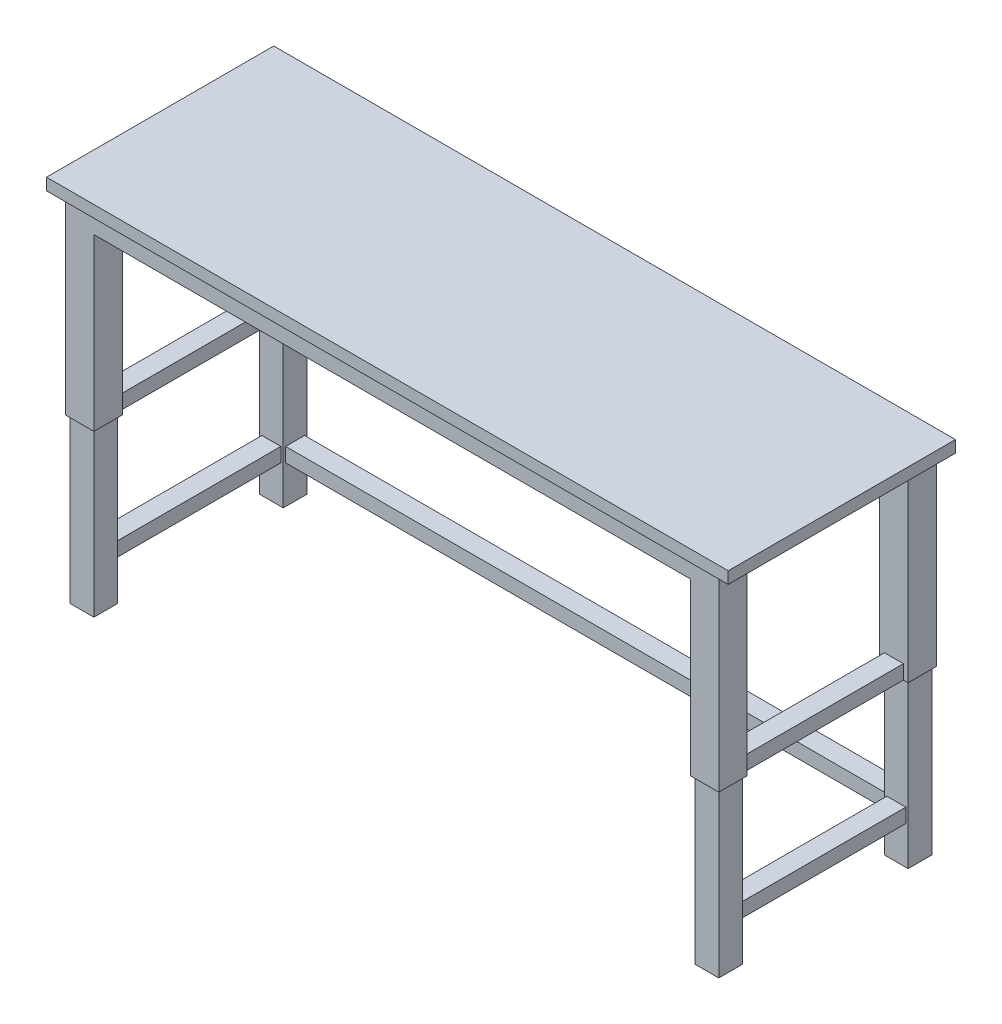
SolidWorks part; units mm, degrees
material "Plain Carbon Steel"
ref_plane "Front Plane" through (0, 0, 0) normal (0, 0, 1) x (1, 0, 0)
ref_plane "Top Plane" through (0, 0, 0) normal (0, 1, 0) x (1, 0, 0)
ref_plane "Right Plane" through (0, 0, 0) normal (1, 0, 0) x (0, 0, -1)
sketch "Sketch1" plane through (0, 0, 0) normal (0, 1, 0) x (1, 0, 0)
  line L1 (-914.4, -304.8) -> (914.4, -304.8)
  line L2 (-914.4, -304.8) -> (-914.4, 304.8)
  line L3 (-914.4, 304.8) -> (914.4, 304.8)
  line L4 (914.4, -304.8) -> (914.4, 304.8)
  line L5 (-914.4, -304.8) -> (914.4, 304.8) construction
  line L6 (-914.4, 304.8) -> (914.4, -304.8) construction
  point P0 (0, 0)
  dimension "D1" = 1828.8
  dimension "D2" = 609.6
extrude "Boss-Extrude1" add sketch "Sketch1" against normal blind 31.75
sketch "Sketch2" plane through (0, 0, 0) normal (1, 0, 0) x (0, 0, -1)
  line L0 (-304.8, -31.75) -> (304.8, -31.75) construction
  line L1 (-292.1, -31.75) -> (-215.9, -31.75)
  line L2 (-292.1, -31.75) -> (-292.1, -82.55)
  line L3 (-292.1, -82.55) -> (-215.9, -82.55)
  line L4 (-215.9, -31.75) -> (-215.9, -82.55)
  line L5 (215.9, -31.75) -> (292.1, -31.75)
  line L6 (215.9, -31.75) -> (215.9, -82.55)
  line L7 (215.9, -82.55) -> (292.1, -82.55)
  line L8 (292.1, -31.75) -> (292.1, -82.55)
  line L9 (-215.9, -31.75) -> (215.9, -31.75) construction
  line L10 (-304.8, -31.75) -> (-304.8, 0) construction
  point P10 (0, -31.75)
  dimension "D1" = 50.8
  dimension "D2" = 76.2
  dimension "D3" = 12.7
extrude "Boss-Extrude2" add sketch "Sketch2" along normal offset from surface 38.1 and the other way offset from surface (876.3 mm away) 38.1 separate body up to face at (914.4, -15.875, 0) other way up to face at (-914.4, -15.875, 0)
sketch "Sketch3" plane through (0, -31.75, 0) normal (0, 1, 0) x (1, 0, 0)
  line L0 (876.3, -215.9) -> (-876.3, -215.9) construction
  line L1 (876.3, -292.1) -> (800.1, -292.1)
  line L2 (876.3, -292.1) -> (876.3, -215.9)
  line L3 (876.3, -215.9) -> (800.1, -215.9)
  line L4 (800.1, -292.1) -> (800.1, -215.9)
  line L5 (876.3, 215.9) -> (-876.3, 215.9) construction
  line L6 (-876.3, -292.1) -> (-800.1, -292.1)
  line L7 (-876.3, -292.1) -> (-876.3, -215.9)
  line L8 (-876.3, -215.9) -> (-800.1, -215.9)
  line L9 (-800.1, -292.1) -> (-800.1, -215.9)
  line L10 (-876.3, 292.1) -> (-800.1, 292.1)
  line L11 (-876.3, 292.1) -> (-876.3, 215.9)
  line L12 (-876.3, 215.9) -> (-800.1, 215.9)
  line L13 (-800.1, 292.1) -> (-800.1, 215.9)
  line L15 (876.3, 292.1) -> (800.1, 292.1)
  line L16 (876.3, 292.1) -> (876.3, 215.9)
  line L17 (876.3, 215.9) -> (800.1, 215.9)
  line L18 (800.1, 292.1) -> (800.1, 215.9)
extrude "Boss-Extrude3" add sketch "Sketch3" against normal blind 508
sketch "Sketch4" plane through (0, 0, 215.9) normal (0, 0, -1) x (-1, 0, 0)
  line L1 (-863.6, -501.65) -> (-812.8, -501.65)
  line L2 (-863.6, -501.65) -> (-863.6, -539.75)
  line L3 (-863.6, -539.75) -> (-812.8, -539.75)
  line L4 (-812.8, -501.65) -> (-812.8, -539.75)
  line L5 (800.1, -539.75) -> (876.3, -539.75) construction
  line L6 (812.8, -539.75) -> (863.6, -539.75)
  line L7 (812.8, -539.75) -> (812.8, -501.65)
  line L8 (812.8, -501.65) -> (863.6, -501.65)
  line L9 (863.6, -539.75) -> (863.6, -501.65)
  line L10 (-876.3, -539.75) -> (-800.1, -539.75) construction
  point P12 (-838.2, -539.75)
  point P14 (838.2, -539.75)
  dimension "D1" = 50.8
  dimension "D2" = 38.1
extrude "Boss-Extrude4" add sketch "Sketch4" along normal up to surface (431.8 mm away) up to face at (0, -298.45, -215.9)
ref_plane "Plane1" through (0, -977.9, 0) normal (0, 1, 0) x (1, 0, 0)
sketch "Sketch6" plane through (0, -977.9, 0) normal (0, 1, 0) x (1, 0, 0)
  line L0 (-806.45, 285.75) -> (-869.95, 285.75)
  line L1 (-869.95, 285.75) -> (-869.95, 222.25)
  line L2 (-869.95, 222.25) -> (-806.45, 222.25)
  line L3 (-806.45, 222.25) -> (-806.45, 285.75)
  line L4 (-800.1, 292.1) -> (-876.3, 292.1)
  line L5 (-800.1, 215.9) -> (-800.1, 292.1)
  line L6 (-876.3, 215.9) -> (-800.1, 215.9)
  line L7 (-876.3, 292.1) -> (-876.3, 215.9)
  line L8 (-800.1, 292.1) -> (-876.3, 292.1) construction
  line L9 (-800.1, 215.9) -> (-800.1, 292.1) construction
  line L10 (-876.3, 215.9) -> (-800.1, 215.9) construction
  line L11 (-876.3, 292.1) -> (-876.3, 215.9) construction
  line L12 (-876.3, -292.1) -> (-800.1, -292.1)
  line L13 (-800.1, -292.1) -> (-800.1, -215.9)
  line L14 (-800.1, -215.9) -> (-876.3, -215.9)
  line L15 (-876.3, -215.9) -> (-876.3, -292.1)
  line L16 (-876.3, -292.1) -> (-800.1, -292.1) construction
  line L17 (-800.1, -292.1) -> (-800.1, -215.9) construction
  line L18 (-800.1, -215.9) -> (-876.3, -215.9) construction
  line L19 (-876.3, -215.9) -> (-876.3, -292.1) construction
  line L20 (800.1, -292.1) -> (876.3, -292.1)
  line L21 (800.1, -215.9) -> (800.1, -292.1)
  line L22 (876.3, -215.9) -> (800.1, -215.9)
  line L23 (876.3, -292.1) -> (876.3, -215.9)
  line L24 (800.1, -292.1) -> (876.3, -292.1) construction
  line L25 (800.1, -215.9) -> (800.1, -292.1) construction
  line L26 (876.3, -215.9) -> (800.1, -215.9) construction
  line L27 (876.3, -292.1) -> (876.3, -215.9) construction
  line L28 (876.3, 292.1) -> (800.1, 292.1)
  line L29 (800.1, 292.1) -> (800.1, 215.9)
  line L30 (800.1, 215.9) -> (876.3, 215.9)
  line L31 (876.3, 215.9) -> (876.3, 292.1)
  line L32 (876.3, 292.1) -> (800.1, 292.1) construction
  line L33 (800.1, 292.1) -> (800.1, 215.9) construction
  line L34 (800.1, 215.9) -> (876.3, 215.9) construction
  line L35 (876.3, 215.9) -> (876.3, 292.1) construction
  line L36 (-869.95, -285.75) -> (-806.45, -285.75)
  line L37 (-806.45, -285.75) -> (-806.45, -222.25)
  line L38 (-806.45, -222.25) -> (-869.95, -222.25)
  line L39 (-869.95, -222.25) -> (-869.95, -285.75)
  line L40 (806.45, -285.75) -> (869.95, -285.75)
  line L41 (869.95, -285.75) -> (869.95, -222.25)
  line L42 (869.95, -222.25) -> (806.45, -222.25)
  line L43 (806.45, -222.25) -> (806.45, -285.75)
  line L44 (869.95, 285.75) -> (806.45, 285.75)
  line L45 (806.45, 285.75) -> (806.45, 222.25)
  line L46 (806.45, 222.25) -> (869.95, 222.25)
  line L47 (869.95, 222.25) -> (869.95, 285.75)
  dimension "D5" = 63.5
  dimension "D1" = 0
  dimension "D2" = 0
  dimension "D3" = 0
  dimension "D4" = 0
extrude "Boss-Extrude5" add sketch "Sketch6" along normal up to surface (438.15 mm away) separate body up to face at (838.2, -539.75, 0)
sketch "Sketch7" plane through (0, 0, 222.25) normal (0, 0, -1) x (-1, 0, 0)
  line L1 (-863.6, -876.3) -> (-812.8, -876.3)
  line L2 (-863.6, -876.3) -> (-863.6, -838.2)
  line L3 (-863.6, -838.2) -> (-812.8, -838.2)
  line L4 (-812.8, -876.3) -> (-812.8, -838.2)
  line L5 (812.8, -876.3) -> (863.6, -876.3)
  line L6 (812.8, -876.3) -> (812.8, -838.2)
  line L7 (812.8, -838.2) -> (863.6, -838.2)
  line L8 (863.6, -876.3) -> (863.6, -838.2)
  line L9 (-863.6, -501.65) -> (-863.6, -539.75) construction
  line L10 (863.6, -539.75) -> (863.6, -501.65) construction
  line L14 (-812.8, -501.65) -> (-863.6, -501.65) construction
  line L15 (-869.95, -977.9) -> (-806.45, -977.9) construction
  dimension "D1" = 101.6
extrude "Boss-Extrude6" add sketch "Sketch7" along normal up to surface (444.5 mm away) up to face at (838.2, -758.825, -222.25)
sketch "Sketch8" plane through (806.45, 0, 0) normal (-1, 0, 0) x (0, 0, 1)
  line L0 (-222.25, -876.3) -> (-222.25, -838.2) construction
  line L1 (-279.4, -876.3) -> (-228.6, -876.3)
  line L2 (-279.4, -876.3) -> (-279.4, -838.2)
  line L3 (-279.4, -838.2) -> (-228.6, -838.2)
  line L4 (-228.6, -876.3) -> (-228.6, -838.2)
  line L5 (-222.25, -876.3) -> (222.25, -876.3) construction
  line L6 (-285.75, -977.9) -> (-222.25, -977.9) construction
  point P10 (-254, -977.9)
  point P11 (-254, -876.3)
  dimension "D1" = 50.8
extrude "Boss-Extrude7" add sketch "Sketch8" along normal up to surface (1612.9 mm away) up to face at (-806.45, -758.825, -254)
